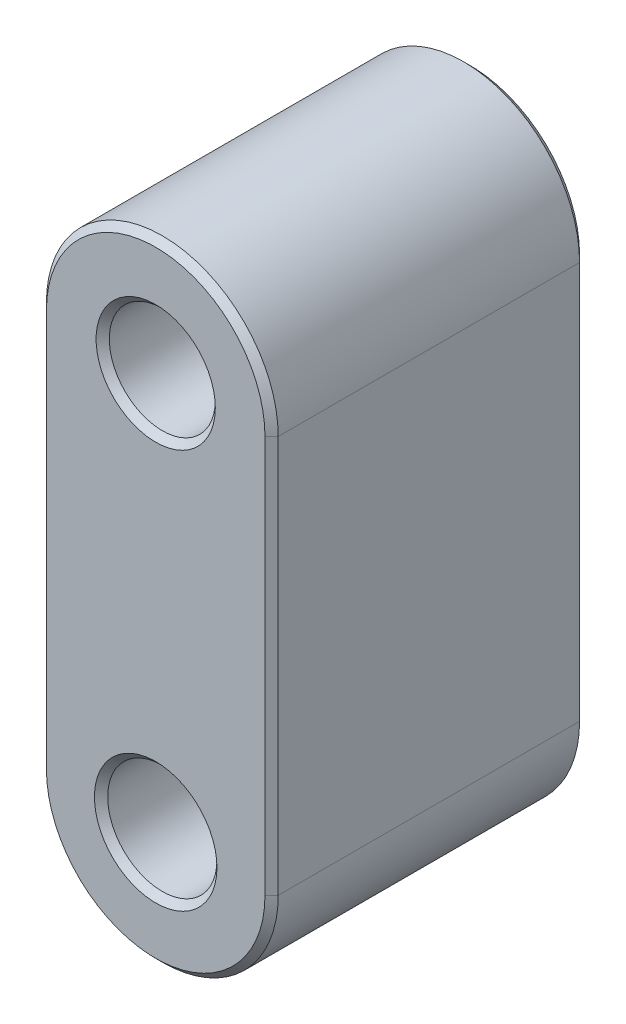
SolidWorks part; units mm, degrees
ref_plane "Front" through (0, 0, 0) normal (0, 0, 1) x (1, 0, 0)
ref_plane "Top" through (0, 0, 0) normal (0, 1, 0) x (1, 0, 0)
ref_plane "Right" through (0, 0, 0) normal (1, 0, 0) x (0, 0, -1)
sketch "Sketch1" plane through (0, 0, 0) normal (0, 0, 1) x (1, 0, 0)
  line L3 (-3.5, 0) -> (-1.6, 0) construction
  line L23 (1.65, -12) -> (3.55, -12) construction
  line L33 (-3.5, 0) -> (-3.5, -12)
  line L34 (3.5, -12) -> (3.5, 0)
  circle A0 centre (0, 0) radius 3.5 construction
  circle A3 centre (0, 0) radius 1.6
  circle A12 centre (0, -12) radius 1.65
  circle A13 centre (0, -12) radius 4.25 construction
  arc A22 (-3.5, 0) -> (3.5, 0) centre (0, 0) cw
  arc A28 (-3.5, -12) -> (3.5, -12) centre (0, -12) ccw
  dimension "D1" = 3.2
  dimension "D3" = 8.5
  dimension "D6" = 3.3
  dimension "D7" = 3.5
  dimension "D2" = 1.9
  dimension "D5" = 12
extrude "Boss-Extrude1" add sketch "Sketch1" along normal mid plane 9.5
sketch "Sketch2" plane through (0, 0, 0) normal (0, 0, 1) x (1, 0, 0)
  line L0 (-3.493, -12.2218) -> (-4.3556, 1.3622)
  line L1 (0, 0) -> (0, 8.0844) construction
  line L2 (0, 0) -> (-0.4318, 1.6114) construction
  line L3 (-0.4318, 1.6114) -> (-1.2941, 4.8296) construction
  line L4 (-1.2941, 4.8296) -> (-1.4494, 5.4092) construction
  line L5 (3.5, 1.6114) -> (3.5, -12)
  line L6 (3.5, -12) -> (3.5, 0) construction
  line L7 (3.5, -12) -> (3.5, 0) construction
  arc A0 (-4.3556, 1.3622) -> (3.5, 1.6114) centre (-0.4318, 1.6114) cw
  circle A1 centre (0, 0) radius 5 construction
  arc A2 (-3.5, -12) -> (3.5, -12) centre (0, -12) ccw construction
  dimension "D2" = 10
  dimension "D1" = 0.6
  dimension "D3" = 15
extrude "Spring" [suppressed] add sketch "Sketch2" along normal through all and the other way through all thin
fillet "Spring Inside Fillets" [suppressed] radius 0.25
chamfer "Deburs" [suppressed] distance 0.2 angle 45
sketch "Sketch3" [suppressed] plane through (-4.0649, -0.1931, 0) normal (-0.9989, -0.0475, 0) x (0, 0, 1)
  line L1 (0, -0.6005) -> (0, -9.4865) construction
  line L6 (4.55, 1.8995) -> (-4.55, 1.8995) construction
  line L8 (4.55, -11.9865) -> (-4.55, -11.9865) construction
  dimension "D1" = 2.5
  dimension "D2" = 2.5
sketch "Sketch4" [suppressed] plane through (-4.0649, -0.1931, 0) normal (-0.9989, -0.0475, 0) x (0, 0, 1)
  line L0 (0, -0.6005) -> (0, -9.4865)
  line L1 (-2, -2.6005) -> (0, -0.6005)
  line L2 (0, -0.6005) -> (2, -2.6005)
  line L3 (0, -0.6005) -> (0, -9.4865) construction
  line L6 (0, -12.0651) -> (0, -0.0719) construction
  dimension "D1" = 45
  dimension "D2" = 2
extrude "Arrow Point" [suppressed] add sketch "Sketch4" along normal blind 0.2 draft 55 thin contours L1 | L2
sketch "Sketch5" [suppressed] plane through (-4.0649, -0.1931, 0) normal (-0.9989, -0.0475, 0) x (0, 0, 1)
  line L0 (0, -1.0045) -> (0, -9.4865)
  line L1 (0, -0.6005) -> (0, -9.4865) construction
extrude "Arrow Shaft" [suppressed] add sketch "Sketch5" along normal blind 0.2 draft 55 thin
chamfer "Deburs no Spring" distance 0.2 angle 45 12 edges at (0, -15.5, -4.75) (3.5, -6, -4.75) (0, 3.5, -4.75) (-3.5, -6, -4.75) (1.65, -12, -4.75) (1.6, 0, -4.75) (0, 3.5, 4.75) (3.5, -6, 4.75) (0, -15.5, 4.75) (-3.5, -6, 4.75) (1.65, -12, 4.75) (1.6, 0, 4.75)
equation "\"D1@Sketch1\"=\"Clearance Hole Diameter@Box Assy.Assembly\"+.05mm"
equation "\"D6@Sketch1\"=\"Clearance Hole Diameter@Box Assy.Assembly\"+.15mm"
